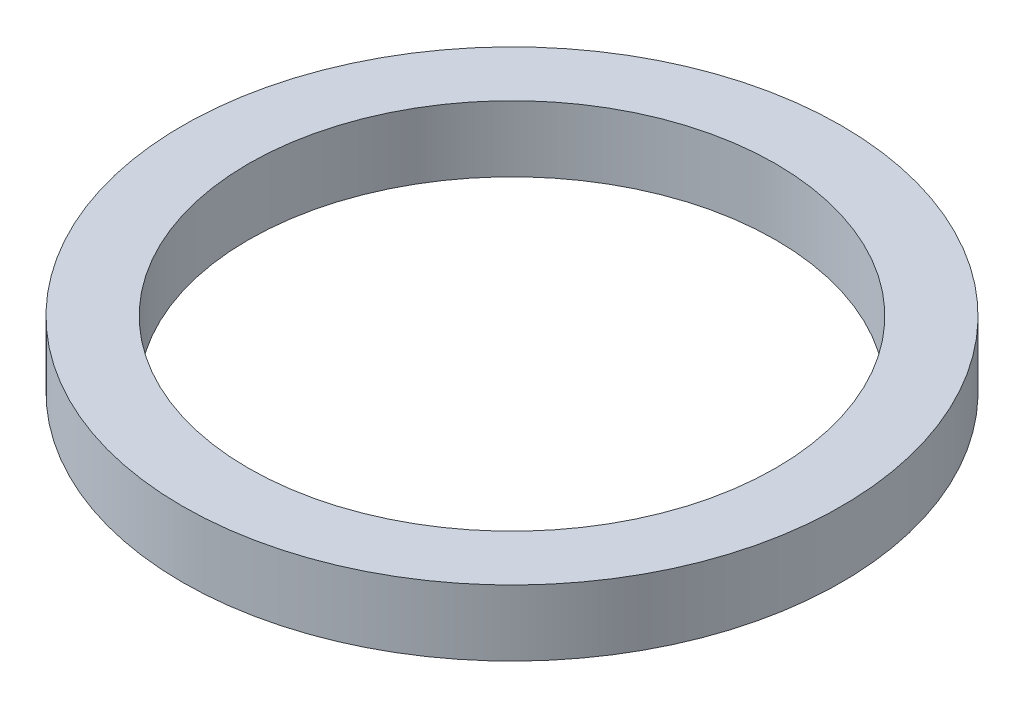
SolidWorks part; units mm, degrees
ref_plane "Alzado" through (0, 0, 0) normal (0, 0, 1) x (1, 0, 0)
ref_plane "Planta" through (0, 0, 0) normal (0, 1, 0) x (1, 0, 0)
ref_plane "Vista lateral" through (0, 0, 0) normal (1, 0, 0) x (0, 0, -1)
sketch "Croquis1" plane through (0, 0, 0) normal (0, 1, 0) x (1, 0, 0)
  circle A0 centre (0, 0) radius 4
  circle A1 centre (0, 0) radius 5
  dimension "D1" = 8
  dimension "D2" = 10
extrude "Saliente-Extruir1" add sketch "Croquis1" along normal blind 1
